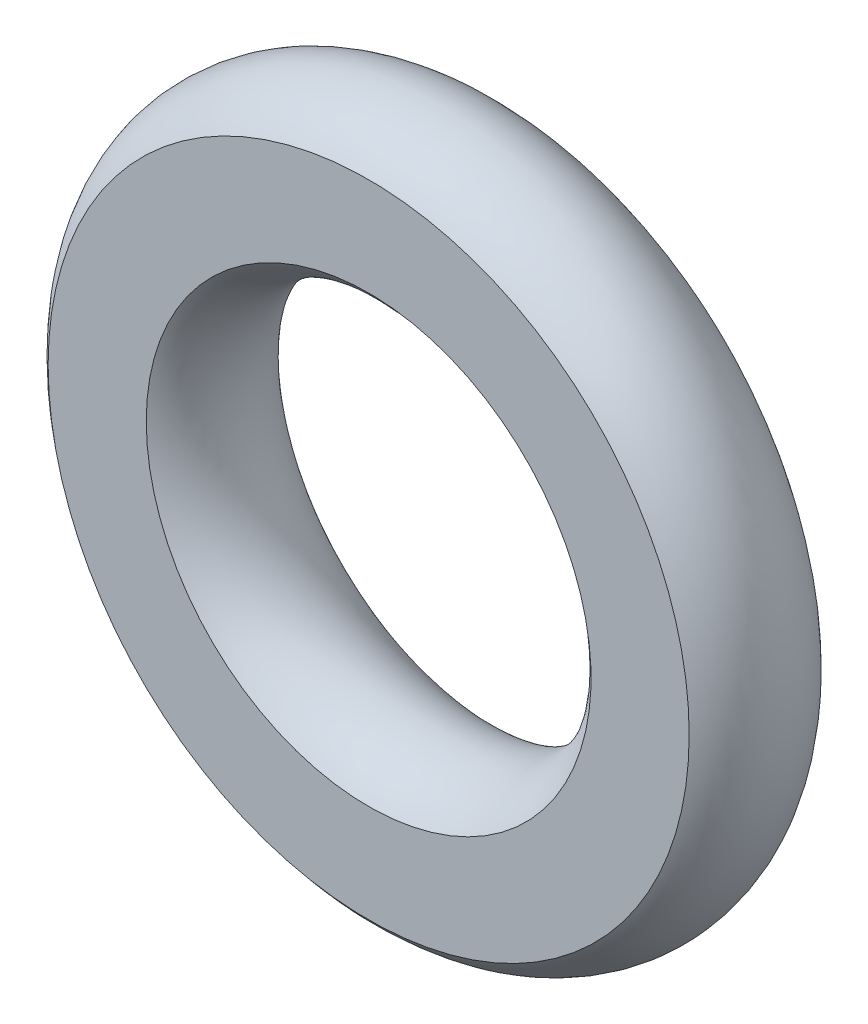
SolidWorks part; units mm, degrees
ref_plane "Front Plane" through (0, 0, 0) normal (0, 0, 1) x (1, 0, 0)
ref_plane "Top Plane" through (0, 0, 0) normal (0, 1, 0) x (1, 0, 0)
ref_plane "Right Plane" through (0, 0, 0) normal (1, 0, 0) x (0, 0, -1)
sketch "Sketch2" plane through (0, 0, 0) normal (0, 1, 0) x (1, 0, 0)
  line L0 (0, 0) -> (1.4732, 0)
  line L1 (0, 0) -> (0, -1.246) construction
  circle A0 centre (2.1082, 0) radius 0.635
  dimension "D3" = 1.27
  dimension "D1" = 1.4732
revolve "Revolve1" add sketch "Sketch2" angle 360 about L1
ref_plane "Plane1" through (0, 0, 0.635) normal (0, 0, 1) x (1, 0, 0)
sketch "Sketch4" plane through (0, 0, 0.635) normal (0, 0, 1) x (1, 0, 0)
  circle A0 centre (0, 0) radius 3.175
  dimension "D1" = 6.35
extrude "Cut-Extrude3" cut sketch "Sketch4" against normal mid plane 0.254 contours A0
